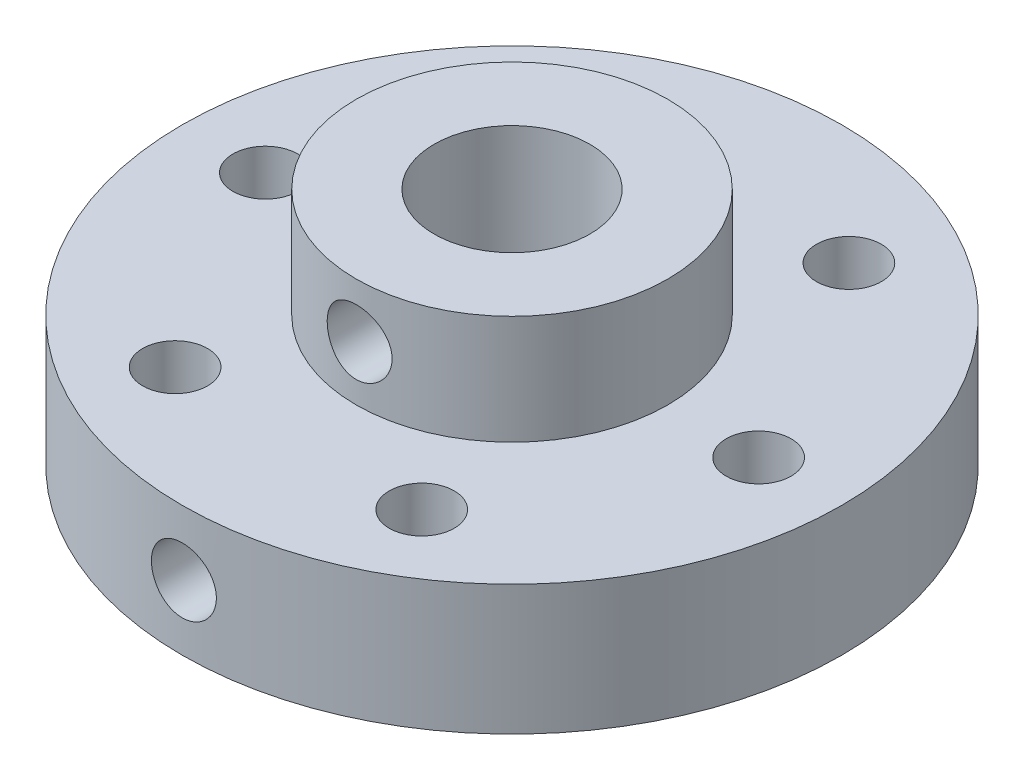
SolidWorks part; units mm, degrees
ref_plane "Front Plane" through (0, 0, 0) normal (0, 0, 1) x (1, 0, 0)
ref_plane "Top Plane" through (0, 0, 0) normal (0, 1, 0) x (1, 0, 0)
ref_plane "Right Plane" through (0, 0, 0) normal (1, 0, 0) x (0, 0, -1)
sketch "Sketch1" plane through (0, 0, 0) normal (0, 0, 1) x (1, 0, 0)
  line L0 (3, 0) -> (3, 9.2)
  line L1 (3, 9.2) -> (6, 9.2)
  line L2 (6, 9.2) -> (6, 5)
  line L3 (6, 5) -> (12.7, 5)
  line L4 (12.7, 5) -> (12.7, 0)
  line L5 (12.7, 0) -> (3, 0)
  line L6 (0, 0) -> (0, 14.7632) construction
  dimension "D1" = 3
  dimension "D2" = 6
  dimension "D3" = 9.2
  dimension "D4" = 5
  dimension "D5" = 12.7
revolve "Revolve1" add sketch "Sketch1" angle 360 about L6
sketch "Sketch4" plane through (0, 5, 0) normal (0, 1, 0) x (1, 0, 0)
  line L0 (-5.06, 0) -> (5.06, 0) construction
  circle A0 centre (0, 0) radius 9.5 construction
  point P5 (-4.75, 8.2272)
  point P13 (4.75, 8.2272)
  point P14 (9.5, 0)
  point P15 (4.75, -8.2272)
  point P16 (-4.75, -8.2272)
  point P17 (-9.5, 0)
  point P20 (-9.4475, -0.9974)
  point P21 (0, 0)
  point P22 (-9.5, 0)
  dimension "D1" = 19
  dimension "D2" = 6
hole_wizard "Tap Drill for M3 Tap1" positions "Sketch4" profile "Sketch3" hole size "M3" standard "DIN" end condition through all
sketch "Sketch3" plane through (-9.5, 5, 0) normal (1, 0, 0) x (0, 0, 1)
  line L0 (0, 0) -> (0, 5)
  line L1 (0, 5) -> (1.25, 5)
  line L2 (1.25, 5) -> (1.25, 0)
  line L5 (1.25, 0) -> (0, 0)
  line L11 (0, -6.35) -> (0, 107.95) construction
  dimension "Thru Hole Dia." = 2.5
  dimension "Thru Hole Depth" = 5
sketch "Sketch7" plane through (0, 0, 0) normal (0, 0, 1) x (1, 0, 0)
  line L0 (0, 9.2) -> (0, 5) construction
  line L1 (6, 9.2) -> (-6, 9.2) construction
  line L2 (12.7, 5) -> (-12.7, 5) construction
  line L3 (0, 5) -> (0, 0) construction
  point P12 (0, 7.1)
  point P14 (0, 2.5)
hole_wizard "Tap Drill for M3 Tap2" positions "Sketch7" profile "Sketch6" hole size "M3" standard "DIN"
sketch "Sketch6" plane through (0, 2.5, 0) normal (1, 0, 0) x (0, 1, 0)
  line L0 (0, 0) -> (0, 12.7)
  line L1 (0, 12.7) -> (1.25, 12.7)
  line L2 (1.25, 12.7) -> (1.25, 0)
  line L5 (1.25, 0) -> (0, 0)
  line L11 (0, -6.35) -> (0, 107.95) construction
  dimension "Thru Hole Dia." = 2.5
  dimension "Thru Hole Depth" = 12.7
